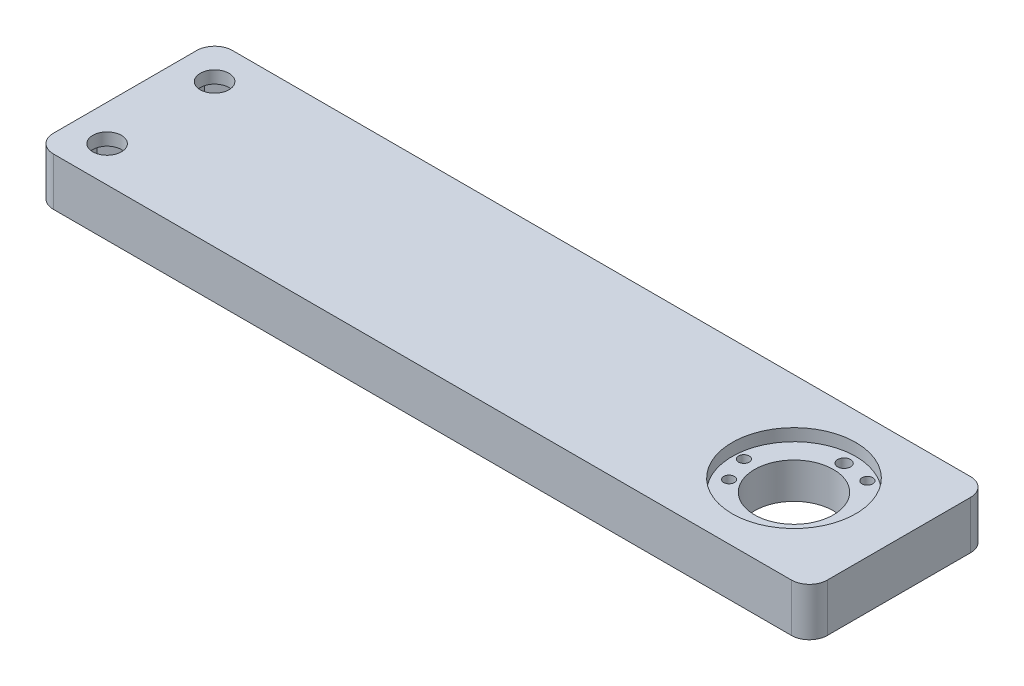
SolidWorks part; units mm, degrees
ref_plane "Front Plane" through (0, 0, 0) normal (0, 0, 1) x (1, 0, 0)
ref_plane "Top Plane" through (0, 0, 0) normal (0, 1, 0) x (1, 0, 0)
ref_plane "Right Plane" through (0, 0, 0) normal (1, 0, 0) x (0, 0, -1)
sketch "Sketch1" plane through (0, 0, 0) normal (0, 1, 0) x (1, 0, 0)
  line L1 (-103, -25) -> (103, -25)
  line L2 (-108, -20) -> (-108, 20)
  line L3 (-103, 25) -> (103, 25)
  line L4 (108, -20) -> (108, 20)
  line L5 (-108, -25) -> (108, 25) construction
  line L6 (-108, 25) -> (108, -25) construction
  arc A0 (103, 25) -> (108, 20) centre (103, 20) cw
  arc A1 (103, -25) -> (108, -20) centre (103, -20) ccw
  arc A2 (-103, -25) -> (-108, -20) centre (-103, -20) cw
  arc A3 (-108, 20) -> (-103, 25) centre (-103, 20) cw
  circle A4 centre (-98, 15) radius 4
  circle A5 centre (-98, -15) radius 4
  circle A6 centre (78.7, 0) radius 11
  circle A7 centre (78.7, 0) radius 19.3
  circle A8 centre (78.7, 14) radius 1.5
  circle A9 centre (86.2, 12.9904) radius 1.5
  circle A10 centre (90.8244, -7) radius 1.5
  circle A11 centre (86.2, -12.9904) radius 1.5
  circle A12 centre (63.7, 1.0089) radius 1.5
  circle A13 centre (66.5756, -5.9911) radius 1.5
  point P0 (0, 0)
  point P28 (78.7, 14)
  point P29 (86.2, 12.9904)
  point P30 (90.8244, -7)
  point P31 (86.2, -12.9904)
  point P32 (66.5756, -5.9911)
  point P33 (63.7, 1.0089)
  dimension "D3" = 5
  dimension "D4" = 8
  dimension "D5" = 8
  dimension "D10" = 22
  dimension "D11" = 38.6
  dimension "D13" = 14
  dimension "D24" = 3
  dimension "D25" = 3
  dimension "D26" = 3
  dimension "D27" = 3
  dimension "D28" = 3
  dimension "D29" = 3
  dimension "D1" = 216
  dimension "D2" = 50
  dimension "D6" = 10
  dimension "D7" = 10
  dimension "D8" = 10
  dimension "D9" = 10
  dimension "D12" = 176.7
  dimension "D14" = 7.5
  dimension "D15" = 12.9904
  dimension "D16" = 7.5677
  dimension "D17" = 12.1244
  dimension "D18" = 7.5
  dimension "D19" = 7.5
  dimension "D20" = 15
  dimension "D21" = 15
  dimension "D22" = 7
  dimension "D23" = 12.1244
extrude "Boss-Extrude1" add sketch "Sketch1" along normal blind 10 contours L3 A0 L4 A1 L1 A2 L2 A3 | A4 | A5 | A6 | A13 | A12 | A8 | A9 | A10 | A11
hole_wizard "CBORE for M3 Hex Socket Head Cap Screw1" positions "Sketch3" profile "Sketch4" counterbore size "M3" standard "ISO" end condition through all
sketch "Sketch3" plane through (0, 10, 0) normal (0, 1, 0) x (1, 0, 0)
  point P0 (78.7, 14)
sketch "Sketch4" plane through (78.7, 10, -14) normal (1, 0, 0) x (0, 0, 1)
  line L0 (0, 0) -> (0, 10)
  line L1 (0, 10) -> (1.8, 10)
  line L3 (1.8, 10) -> (1.8, 3.4)
  line L4 (3.25, 3.4) -> (1.8, 3.4)
  line L5 (3.25, 3.4) -> (3.25, 0.025)
  line L6 (3.25, 0.025) -> (3.275, 0)
  line L7 (3.275, 0) -> (0, 0)
  line L8 (-3.25, 0.025) -> (-3.275, 0) construction
  line L11 (0, -6.35) -> (0, 107.95) construction
  dimension "Thru Hole Dia." = 3.6
  dimension "Thru Hole Depth" = 10
  dimension "C'Bore Dia." = 6.5
  dimension "C'Bore Depth" = 3.4
  dimension "Near C'Sink Dia." = 6.55
  dimension "Near C'Sink Angle" = 90
sketch "Sketch5" plane through (0, 10, 0) normal (0, 1, 0) x (1, 0, 0)
  circle A0 centre (78.7, 0) radius 17.25
  dimension "D1" = 34.5
extrude "Cut-Extrude1" cut sketch "Sketch5" against normal up to surface (3.4 mm away) up to face at (78.7, 6.6, -14.125)
sketch "Sketch6" plane through (0, 0, 0) normal (0, -1, 0) x (1, 0, 0)
  line L0 (-78, 25) -> (-78, -25)
  line L4 (-103, -25) -> (103, -25)
  line L5 (108, -20) -> (108, 20)
  line L6 (103, 25) -> (-103, 25)
  line L7 (-108, 20) -> (-108, -20)
  line L8 (-103, -25) -> (103, -25)
  line L9 (108, -20) -> (108, 20)
  line L10 (103, 25) -> (-103, 25)
  line L11 (-108, 20) -> (-108, -20)
  circle A0 centre (-98, 15) radius 4 construction
  circle A1 centre (-98, -15) radius 4 construction
  circle A2 centre (63.7, -1.0089) radius 1.5 construction
  circle A3 centre (66.5756, 5.9911) radius 1.5 construction
  arc A4 (-108, -20) -> (-103, -25) centre (-103, -20) ccw
  arc A5 (103, -25) -> (108, -20) centre (103, -20) ccw
  arc A6 (108, 20) -> (103, 25) centre (103, 20) ccw
  arc A7 (-103, 25) -> (-108, 20) centre (-103, 20) ccw
  arc A8 (-108, -20) -> (-103, -25) centre (-103, -20) ccw
  arc A9 (103, -25) -> (108, -20) centre (103, -20) ccw
  arc A10 (108, 20) -> (103, 25) centre (103, 20) ccw
  arc A11 (-103, 25) -> (-108, 20) centre (-103, 20) ccw
  circle A12 centre (78.7, 0) radius 11 construction
  circle A13 centre (86.2, 12.9904) radius 1.5 construction
  circle A14 centre (90.8244, 7) radius 1.5 construction
  circle A15 centre (86.2, -12.9904) radius 1.5 construction
  circle A16 centre (78.7, -14) radius 1.8 construction
  circle A17 centre (78.7, -14) radius 1.8
  circle A18 centre (86.2, -12.9904) radius 1.5
  circle A19 centre (90.8244, 7) radius 1.5
  circle A20 centre (86.2, 12.9904) radius 1.5
  circle A21 centre (78.7, 0) radius 11
  circle A22 centre (66.5756, 5.9911) radius 1.5
  circle A23 centre (63.7, -1.0089) radius 1.5
  circle A24 centre (-98, -15) radius 4
  circle A25 centre (-98, 15) radius 4
  circle M10 centre (78.7, -14) radius 1.8
  circle M11 centre (90.8244, 7) radius 1.5
  circle M12 centre (66.5756, 5.9911) radius 1.5
  circle M13 centre (-98, 15) radius 4
  arc M14 (-108, -20) -> (-103, -25) centre (-103, -20) ccw
  line M15 (-103, -25) -> (103, -25)
  arc M16 (103, -25) -> (108, -20) centre (103, -20) ccw
  line M17 (108, -20) -> (108, 20)
  arc M18 (108, 20) -> (103, 25) centre (103, 20) ccw
  line M19 (103, 25) -> (-103, 25)
  arc M20 (-103, 25) -> (-108, 20) centre (-103, 20) ccw
  line M21 (-108, 20) -> (-108, -20)
  circle M22 centre (-98, -15) radius 4
  circle M23 centre (78.7, 0) radius 11
  circle M24 centre (63.7, -1.0089) radius 1.5
  circle M25 centre (86.2, -12.9904) radius 1.5
  circle M26 centre (86.2, 12.9904) radius 1.5
  dimension "D2" = 30
  dimension "D1" = 0
extrude "Boss-Extrude2" add sketch "Sketch6" along normal blind 3.4 contours L0 M19 M15 M16 M17 M18 M10 M12 M23 M25 M26 M24 M11 | L0 M19 M20 M21 M14 M15 M13 M22 | A8 L8 A9 L9 A10 L10 A11 L11
ref_plane "Plane1" through (0, 3.3, 0) normal (0, 1, 0) x (1, 0, 0)
sketch "Sketch7" plane through (0, 3.3, 0) normal (0, 1, 0) x (1, 0, 0)
  line L0 (-108, -20) -> (-108, 20) construction
  line L1 (-91.3, 11.1318) -> (-91.3, 18.8682)
  line L2 (-91.3, 18.8682) -> (-98, 22.7365)
  line L3 (-98, 22.7365) -> (-104.7, 18.8682)
  line L4 (-104.7, 18.8682) -> (-104.7, 11.1318)
  line L5 (-104.7, 11.1318) -> (-98, 7.2635)
  line L6 (-98, 7.2635) -> (-91.3, 11.1318)
  line L7 (-91.3, -18.8682) -> (-91.3, -11.1318)
  line L8 (-91.3, -11.1318) -> (-98, -7.2635)
  line L9 (-98, -7.2635) -> (-104.7, -11.1318)
  line L10 (-104.7, -11.1318) -> (-104.7, -18.8682)
  line L11 (-104.7, -18.8682) -> (-98, -22.7365)
  line L12 (-98, -22.7365) -> (-91.3, -18.8682)
  circle A0 centre (-98, 15) radius 6.7 construction
  circle A1 centre (-98, -15) radius 6.7 construction
  point P20 (-91.3, 15)
  dimension "D1" = 13.4
extrude "Cut-Extrude2" cut sketch "Sketch7" against normal blind 3.75 and the other way blind 3.25
